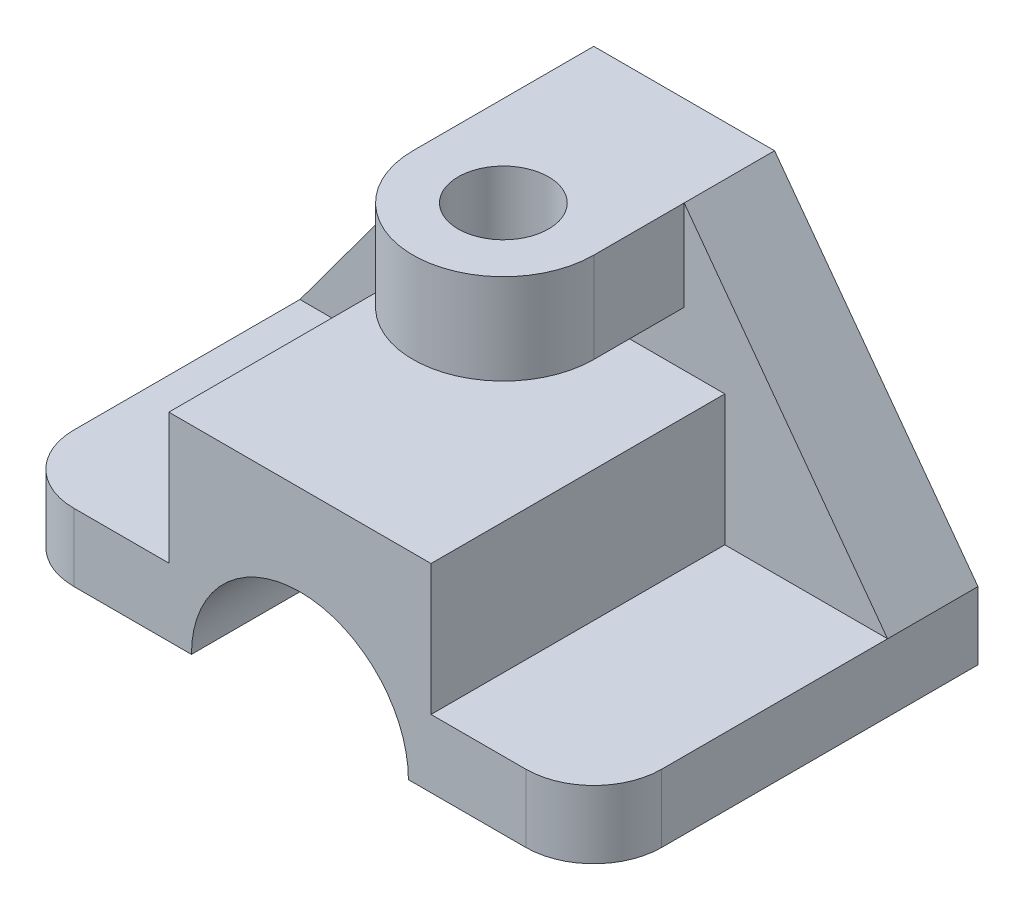
SolidWorks part; units mm, degrees
ref_plane "정면" through (0, 0, 0) normal (0, 0, 1) x (1, 0, 0)
ref_plane "윗면" through (0, 0, 0) normal (0, 1, 0) x (1, 0, 0)
ref_plane "우측면" through (0, 0, 0) normal (1, 0, 0) x (0, 0, -1)
sketch "스케치1" plane through (0, 0, 0) normal (0, 0, 1) x (1, 0, 0)
  line L0 (-65, 0) -> (65, 0)
  line L1 (65, 0) -> (65, 15)
  line L2 (65, 15) -> (29, 15)
  line L3 (29, 15) -> (29, 43.9178)
  line L4 (29, 43.9178) -> (-29, 43.9178)
  line L5 (-29, 43.9178) -> (-29, 15)
  line L6 (-29, 15) -> (-65, 15)
  line L7 (-65, 15) -> (-65, 0)
  dimension "D1" = 130
  dimension "D2" = 15
  dimension "D3" = 58
  dimension "D4" = 36
extrude "보스-돌출1" add sketch "스케치1" along normal blind 85
sketch "스케치2" plane through (0, 0, 85) normal (0, 0, 1) x (1, 0, 0)
  line L0 (-65, 0) -> (65, 0) construction
  line L1 (-24, 0) -> (24, 0)
  line L10 (-65, 15) -> (-65, 0)
  line L11 (-65, 0) -> (65, 0)
  line L12 (65, 0) -> (65, 15)
  line L13 (65, 15) -> (29, 15)
  line L14 (29, 15) -> (29, 43.9178)
  line L15 (29, 43.9178) -> (-29, 43.9178)
  line L16 (-29, 43.9178) -> (-29, 15)
  line L17 (-29, 15) -> (-65, 15)
  line L18 (-65, 15) -> (-65, 0)
  line L19 (-24, 0) -> (24, 0)
  line L20 (65, 0) -> (65, 15)
  line L21 (65, 15) -> (29, 15)
  line L22 (29, 15) -> (29, 43.9178)
  line L23 (29, 43.9178) -> (-29, 43.9178)
  line L24 (-29, 43.9178) -> (-29, 15)
  line L25 (-29, 15) -> (-65, 15)
  arc A0 (24, 0) -> (-24, 0) centre (0, 0) ccw
  dimension "D1" = 48
  dimension "D2" = 0
extrude "컷-돌출1" cut sketch "스케치2" against normal through all and the other way through all contours A0
sketch "스케치4" plane through (0, 0, 0) normal (0, 0, -1) x (-1, 0, 0)
  line L0 (-65, 15) -> (-20, 76)
  line L1 (-20, 76) -> (20, 76)
  line L2 (20, 76) -> (65, 15)
  line L3 (65, 15) -> (29, 15)
  line L4 (29, 15) -> (29, 43.9178)
  line L5 (29, 43.9178) -> (-29, 43.9178)
  line L6 (-29, 43.9178) -> (-29, 15)
  line L7 (-29, 15) -> (-65, 15)
  dimension "D1" = 61
  dimension "D2" = 40
extrude "보스-돌출2" add sketch "스케치4" against normal blind 20
sketch "스케치5" plane through (0, 76, 0) normal (0, 1, 0) x (1, 0, 0)
  line L0 (-20, 0) -> (-20, -40)
  line L1 (20, 0) -> (20, -40)
  line L2 (-20, 0) -> (20, 0)
  arc A1 (-20, -40) -> (20, -40) centre (0, -40) ccw
  circle A2 centre (0, -40) radius 10
  dimension "D1" = 40
  dimension "D2" = 20
  dimension "D3" = 20
extrude "보스-돌출3" add sketch "스케치5" against normal blind 20
fillet "필렛1" radius 15 2 edges at (65, 7.5, 85) (-65, 7.5, 85)
